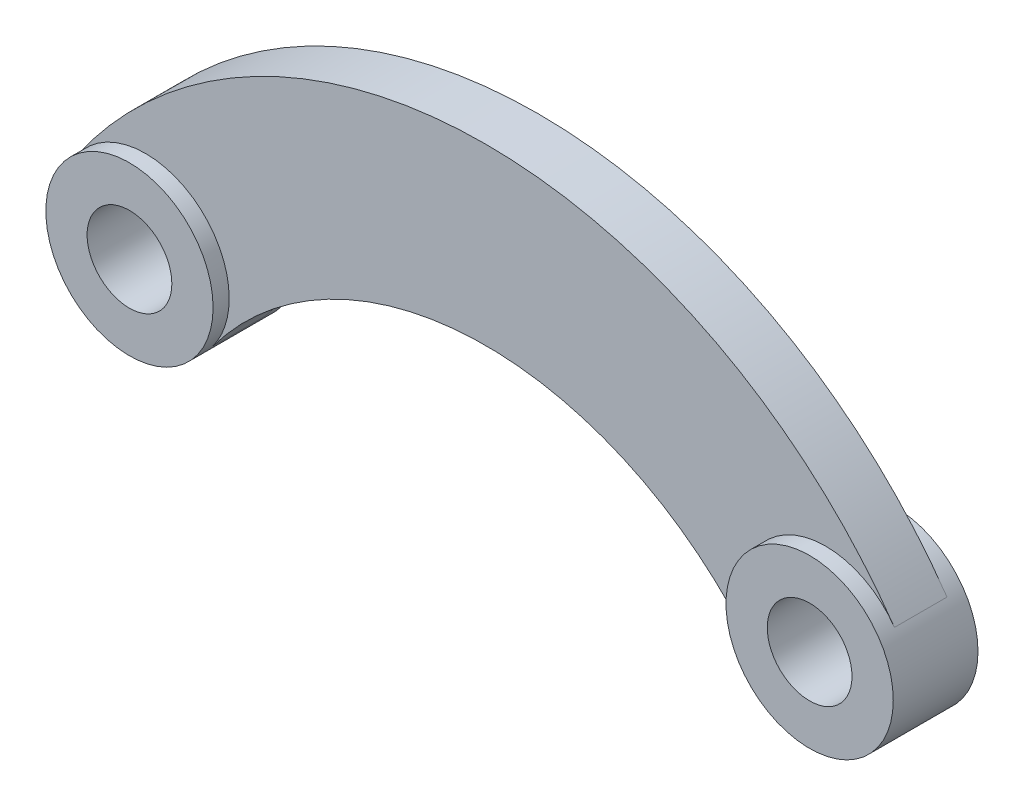
SolidWorks part; units mm, degrees
ref_plane "Front Plane" through (0, 0, 0) normal (0, 0, 1) x (1, 0, 0)
ref_plane "Top Plane" through (0, 0, 0) normal (0, 1, 0) x (1, 0, 0)
ref_plane "Right Plane" through (0, 0, 0) normal (1, 0, 0) x (0, 0, -1)
sketch "Sketch1" plane through (0, 0, 0) normal (0, 0, 1) x (1, 0, 0)
  line L0 (0, 0) -> (610, 0) construction
  circle A0 centre (0, 0) radius 75
  circle A1 centre (0, 0) radius 38
  circle A2 centre (610, 0) radius 75
  circle A3 centre (610, 0) radius 38
  point P10 (685, 0)
  point P11 (-75, 0)
  dimension "D2" = 150
  dimension "D3" = 76
  dimension "D4" = 150
  dimension "D5" = 76
  dimension "D1" = 610
extrude "Boss-Extrude1" add sketch "Sketch1" against normal mid plane 76
sketch "Sketch2" plane through (0, 0, 0) normal (0, 0, 1) x (1, 0, 0)
  arc A0 (60.1974, -44.7356) -> (549.8026, -44.7356) centre (305, -226.6605) cw
  circle A1 centre (0, 0) radius 75 construction
  circle A2 centre (610, 0) radius 75 construction
  circle A3 centre (610, 0) radius 75
  circle A4 centre (0, 0) radius 75
  arc A5 (-61.6577, 42.7005) -> (671.6577, 42.7005) centre (305, -211.225) cw
  dimension "D1" = 305
  dimension "D2" = 446
extrude "Boss-Extrude2" add sketch "Sketch2" along normal mid plane 47.1487 contours A5 A4 A0 A3
